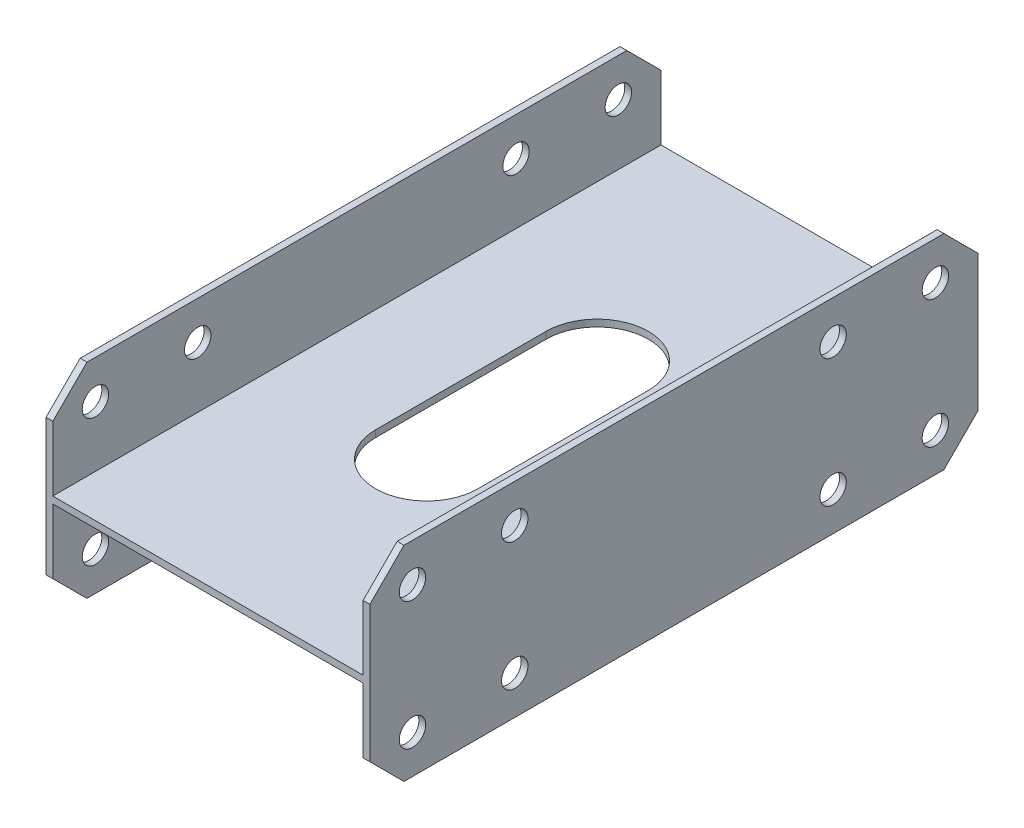
SolidWorks part; units mm, degrees
ref_plane "前视基准面" through (0, 0, 0) normal (0, 0, 1) x (1, 0, 0)
ref_plane "上视基准面" through (0, 0, 0) normal (0, 1, 0) x (1, 0, 0)
ref_plane "右视基准面" through (0, 0, 0) normal (1, 0, 0) x (0, 0, -1)
sketch "草图1" plane through (0, 0, 0) normal (0, 0, 1) x (1, 0, 0)
  line L0 (-1000, 0) -> (49000, 0) construction
  line L1 (0, -1000) -> (0, 49000) construction
  line L3 (-190, 120) -> (190, 120)
  line L4 (-190, 120) -> (-190, -120)
  line L5 (-190, -120) -> (190, -120)
  line L6 (190, 120) -> (190, -120)
  line L7 (-182, 120) -> (182, 120)
  line L8 (-182, 120) -> (-182, 4)
  line L9 (-182, 4) -> (182, 4)
  line L10 (182, 120) -> (182, 4)
  line L11 (-182, -4) -> (182, -4)
  line L12 (-182, -4) -> (-182, -120)
  line L13 (-182, -120) -> (182, -120)
  line L14 (182, -4) -> (182, -120)
  dimension "D1" = 8
  dimension "D2" = 8
  dimension "D3" = 240
  dimension "D4" = 120
  dimension "D5" = 380
  dimension "D6" = 190
  dimension "D7" = 8
  dimension "D8" = 4
extrude "拉伸1" add sketch "草图1" along normal blind 713.5 contours L11 L14 L5 L6 L3 L10 L9 L8 L4 L12
sketch "草图2" plane through (190, 0, 0) normal (1, 0, 0) x (0, 0, -1)
  line L0 (-1713.5, 0) -> (48286.5, 0) construction
  line L1 (-356.75, -880) -> (-356.75, 49120) construction
  line L2 (-713.5, 120) -> (0, 120) construction
  line L3 (-713.5, 120) -> (-713.5, -120) construction
  line L4 (-663.5, 75) -> (-543.5, 75) construction
  line L5 (-663.5, 75) -> (-663.5, -75) construction
  line L6 (-663.5, 75) -> (-170, 75) construction
  line L8 (-673.5, 120) -> (-713.5, 80)
  line L9 (-40, 120) -> (0, 80)
  line L10 (-40, -120) -> (0, -80)
  line L11 (-673.5, -120) -> (-713.5, -80)
  line L12 (-713.5, 80) -> (-713.5, 120)
  line L13 (-713.5, 120) -> (-673.5, 120)
  line L14 (-713.5, -80) -> (-713.5, -120)
  line L15 (-713.5, -120) -> (-673.5, -120)
  line L16 (-40, -120) -> (0, -120)
  line L17 (0, -120) -> (0, -80)
  line L18 (0, 80) -> (0, 120)
  line L19 (0, 120) -> (-40, 120)
  circle A0 centre (-663.5, 75) radius 15.5
  circle A1 centre (-543.5, 75) radius 15.5
  circle A2 centre (-663.5, -75) radius 15.5
  circle A3 centre (-543.5, -75) radius 15.5
  circle A4 centre (-170, 75) radius 15.5
  circle A5 centre (-50, 75) radius 15.5
  circle A6 centre (-50, -75) radius 15.5
  circle A7 centre (-170, -75) radius 15.5
  point P8 (-356.75, 120)
  point P37 (-713.5, 0)
  dimension "D1" = 31
  dimension "D2" = 50
  dimension "D3" = 45
  dimension "D4" = 120
  dimension "D5" = 150
  dimension "D6" = 493.5
  dimension "D7" = 40
  dimension "D8" = 40
extrude "拉伸2" cut sketch "草图2" against normal through all
sketch "草图3" plane through (0, 4, 0) normal (0, 1, 0) x (1, 0, 0)
  line L0 (0, -1000) -> (0, 49000) construction
  line L1 (0, -256.75) -> (0, -456.75) construction
  line L2 (60, -256.75) -> (60, -456.75)
  line L3 (-60, -256.75) -> (-60, -456.75)
  line L4 (-1182, -356.75) -> (48818, -356.75) construction
  line L5 (-182, -673.5) -> (-182, -40) construction
  arc A0 (60, -256.75) -> (-60, -256.75) centre (0, -256.75) ccw
  arc A1 (-60, -456.75) -> (60, -456.75) centre (0, -456.75) ccw
  point P5 (0, -356.75)
  point P15 (-182, -356.75)
  dimension "D1" = 120
  dimension "D2" = 200
  dimension "D3" = 100
extrude "拉伸3" cut sketch "草图3" against normal through all
